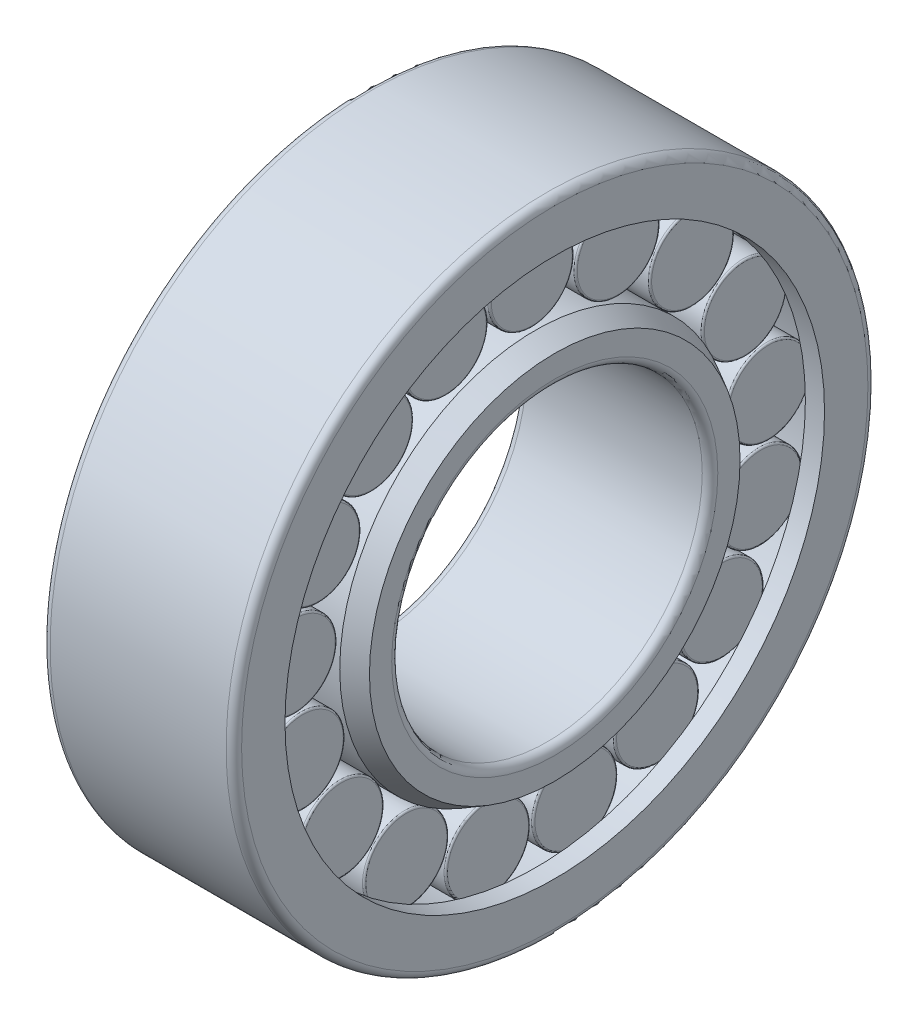
SolidWorks part; units mm, degrees
ref_plane "Plane1" through (0, 0, 0) normal (0, 0, 1) x (1, 0, 0)
ref_plane "Plane2" through (0, 0, 0) normal (0, 1, 0) x (1, 0, 0)
ref_plane "Plane3" through (0, 0, 0) normal (1, 0, 0) x (0, 0, -1)
sketch "Clipboard" plane through (0, 0, 0) normal (0, 0, 1) x (1, 0, 0)
  line L0 (-10, 0) -> (10, 0) construction
  line L1 (0, 0) -> (361.8657, -110.6335)
  line L2 (0, 0) -> (229.965, -4.0141)
  line L3 (0, 0) -> (541.5175, 9.4522)
  line L4 (0, 0) -> (-22.3573, -0.3902)
  dimension "CLdia" = 230
  dimension "Count" = 359
  dimension "Show_count" = 359
  dimension "Max_count" = 17
  dimension "Min_count" = 1
  dimension "Race_OD" = 541.6
  dimension "Race_ID" = 378.4
sketch "OutRacSke" plane through (0, 0, 0) normal (0, 0, 1) x (1, 0, 0)
  line L0 (-74, 260.6) -> (-92.5, 260.6)
  line L1 (-92.5, 260.6) -> (-92.5, 302.5)
  line L2 (-85, 310) -> (85, 310)
  line L3 (92.5, 302.5) -> (92.5, 260.6)
  line L4 (92.5, 260.6) -> (74, 260.6)
  line L5 (74, 260.6) -> (74, 270.8)
  line L6 (74, 270.8) -> (-74, 270.8)
  line L7 (-74, 270.8) -> (-74, 260.6)
  line L8 (-90, 0) -> (90, 0) construction
  arc A0 (-92.5, 302.5) -> (-85, 310) centre (-85, 302.5) cw
  arc A1 (85, 310) -> (92.5, 302.5) centre (85, 302.5) cw
  dimension "Race_OD" = 541.6
  dimension "radius" = 7.5
  dimension "OD" = 620
  dimension "Cyl_Len" = 148
  dimension "halfCylLen" = 74
  dimension "Width" = 185
  dimension "halfWidth" = 92.5
  dimension "groove_dp" = 10.2
revolve "OuterRace" add sketch "OutRacSke" angle 360 about L8
sketch "RolDetSke" plane through (0, 0, 0) normal (0, 0, 1) x (1, 0, 0)
  line L0 (-70.3, 269.1728) -> (-70.3, 230)
  line L1 (-70.3, 230) -> (70.3, 230)
  line L2 (70.3, 230) -> (70.3, 269.1728)
  line L3 (68.6678, 270.805) -> (-68.6678, 270.805)
  line L4 (-33.6, 230) -> (33.6, 230) construction
  arc A0 (70.3, 269.1728) -> (68.6678, 270.805) centre (68.6678, 269.1728) ccw
  arc A1 (-68.6678, 270.805) -> (-70.3, 269.1728) centre (-68.6678, 269.1728) ccw
  dimension "radius" = 1.6322
  dimension "RolCLRad" = 230
  dimension "Length" = 140.6
  dimension "halfLength" = 70.3
  dimension "Roller_diameter" = 81.61
revolve "RollerDetailed" add sketch "RolDetSke" angle 360 about L4
ref_axis "Axis1" through (-50, 0, 0) along (1, 0, 0)
sketch "RolSimSke" plane through (0, 101.6, 0) normal (0, 0, 1) x (1, 0, 0)
  line L0 (-70.3, 167.5728) -> (-70.3, 89.2272)
  line L1 (25.4, -101.6) -> (-25.4, -101.6) construction
  line L2 (70.3, 89.2272) -> (70.3, 167.5728)
  line L3 (68.6678, 169.205) -> (-68.6678, 169.205)
  line L5 (68.6678, 87.595) -> (-68.6678, 87.595)
  arc A0 (70.3, 167.5728) -> (68.6678, 169.205) centre (68.6678, 167.5728) ccw
  arc A1 (-68.6678, 169.205) -> (-70.3, 167.5728) centre (-68.6678, 167.5728) ccw
  arc A2 (70.3, 89.2272) -> (68.6678, 87.595) centre (68.6678, 89.2272) cw
  arc A3 (-68.6678, 87.595) -> (-70.3, 89.2272) centre (-68.6678, 89.2272) cw
  dimension "halfLength" = 70.3
  dimension "Roller_diameter" = 81.61
  dimension "radius" = 1.6322
  dimension "D1" = 189.195
  dimension "Rol_Length" = 140.6
revolve "RollersSimplified" [suppressed] add sketch "RolSimSke" angle 360 about L1
sketch "InsRacSke" plane through (0, 0, 0) normal (0, 0, 1) x (1, 0, 0)
  line L0 (-74, 189.2) -> (-92.5, 179)
  line L1 (-92.5, 179) -> (-92.5, 157.5)
  line L2 (-85, 150) -> (85, 150)
  line L3 (92.5, 157.5) -> (92.5, 179)
  line L4 (92.5, 179) -> (74, 189.2)
  line L5 (74, 189.2) -> (-74, 189.2)
  line L6 (-90, 0) -> (90, 0) construction
  line L7 (0, 0) -> (0, 127) construction
  arc A0 (-92.5, 157.5) -> (-85, 150) centre (-85, 157.5) ccw
  arc A1 (85, 150) -> (92.5, 157.5) centre (85, 157.5) ccw
  dimension "Race_ID" = 378.4
  dimension "radius" = 7.5
  dimension "Cyl_Len" = 148
  dimension "Width" = 185
  dimension "groove_dp" = 10.2
  dimension "Bore" = 300
revolve "InnerRace" add sketch "InsRacSke" angle 360 about L6
pattern_circular "RollersDetailed" count 17 every 21.176 about axis through (-50, 0, 0) along (1, 0, 0) of "RollerDetailed"
sketch "CagSpiSke" plane through (0, 0, 0) normal (0, 0, 1) x (1, 0, 0)
  line L0 (83.25, 219.7987) -> (83.25, 240.2013)
  line L1 (83.25, 240.2013) -> (-83.25, 240.2012)
  line L2 (-83.25, 240.2012) -> (-83.25, 219.7987)
  line L3 (-83.25, 219.7987) -> (83.25, 219.7987)
  line L4 (-90, 0) -> (90, 0) construction
  dimension "Cag_IR" = 439.5975
  dimension "thickness" = 20.4025
  dimension "width" = 166.5
  dimension "halfwidth" = 83.25
revolve "CageSpine" [suppressed] add sketch "CagSpiSke" angle 0.001 about L4
equation "\"CLdia@Clipboard\" =  ( \"Race_OD@Clipboard\" + \"Race_ID@Clipboard\" )  / 4"
equation "\"Race_OD@OutRacSke\" = \"Race_OD@Clipboard\""
equation "\"halfCylLen@OutRacSke\" = \"Cyl_Len@OutRacSke\" / 2"
equation "\"RolCLRad@RolDetSke\" = \"CLdia@Clipboard\""
equation "\"Roller_diameter@RolDetSke\" =  ( \"Race_OD@Clipboard\" - \"Race_ID@Clipboard\" )  / 2 + .01"
equation "\"Roller_diameter@RolSimSke\" =  ( \"Race_OD@Clipboard\" - \"Race_ID@Clipboard\" )  / 2 + .01"
equation "\"radius@RolDetSke\" = \"Roller_diameter@RolDetSke\" / 50"
equation "\"Length@RolDetSke\" = \"Cyl_Len@OutRacSke\" * .95"
equation "\"halfLength@RolDetSke\" = \"Length@RolDetSke\" / 2"
equation "\"thickness@CagSpiSke\"  = \"Roller_diameter@RolDetSke\" * 0.25"
equation "\"Cag_IR@CagSpiSke\" =  \"RolCLRad@RolDetSke\" * 2 - \"thickness@CagSpiSke\""
equation "\"Rol_Length@RolSimSke\" = \"Cyl_Len@OutRacSke\" * .95"
equation "\"halfLength@RolSimSke\" = \"Rol_Length@RolSimSke\" / 2"
equation "\"radius@RolSimSke\" = \"radius@RolDetSke\""
equation "\"D1@RolSimSke\" = \"CLdia@Clipboard\" -  ( \"Roller_diameter@RolSimSke\" / 2 ) "
equation "\"Max_count@Clipboard\" = int( 3.14159265 / atn(( \"Roller_diameter@RolDetSke\" / 2) / sqr( \"RolCLRad@RolDetSke\"  *  \"RolCLRad@RolDetSke\" - ( \"Roller_diameter@RolDetSke\" / 2) *  ( \"Roller_diameter@RolDetSke\" / 2))))"
equation "\"Max_count@Clipboard\" = ((sgn( \"Max_count@Clipboard\" - \"Count@Clipboard\" )-1)*( \"Max_count@Clipboard\" - \"Count@Clipboard\" ))/-2+ \"Count@Clipboard\""
equation "\"Count@RollersDetailed\" = int( \"Show_count@Clipboard\" ) "
equation "\"Count@RollersDetailed\" = ((sgn( \"Count@RollersDetailed\" - \"Max_count@Clipboard\" )-1)*( \"Count@RollersDetailed\" - \"Max_count@Clipboard\" ))/-2+ \"Max_count@Clipboard\""
equation "\"Count@RollersDetailed\" = ((sgn( \"Count@RollersDetailed\" - \"Min_count@Clipboard\" )+1)*( \"Count@RollersDetailed\" - \"Min_count@Clipboard\"))/2 +\"Min_count@Clipboard\""
equation "\"Angle@RollersDetailed\" = 360.0 / \"Max_count@Clipboard\""
equation "\"halfWidth@OutRacSke\" = \"Width@OutRacSke\" / 2"
equation "\"radius@InsRacSke\" = \"radius@OutRacSke\" "
equation "\"groove_dp@InsRacSke\" = \"groove_dp@OutRacSke\""
equation "\"Width@InsRacSke\" = \"Width@OutRacSke\""
equation "' \"halfWidth@InsRacSke\" = \"Width@OutRacSke\" / 2"
equation "\"Race_ID@InsRacSke\" = \"Race_ID@Clipboard\""
equation "\"Cyl_Len@InsRacSke\" = \"Cyl_Len@OutRacSke\""
equation "\"Angle@CageSpine\" =  \"Angle@RollersDetailed\" * ( \"Count@RollersDetailed\" -1 + int( \"Count@RollersDetailed\" / \"Max_count@Clipboard\" ) )  + 0.001 -  int( \"Count@RollersDetailed\" / \"Max_count@Clipboard\" ) * 0.001"
equation "\"Angle@CageSpine\" =  \"Angle@CageSpine\" * int( \"Min_count@Clipboard\" / 2) + int(1 / \"Min_count@Clipboard\")  * 0.001"
equation "\"width@CagSpiSke\" =   ( \"Width@InsRacSke\" + \"Cyl_Len@InsRacSke\" )  / 2"
equation "\"halfwidth@CagSpiSke\" = \"width@CagSpiSke\" / 2"
